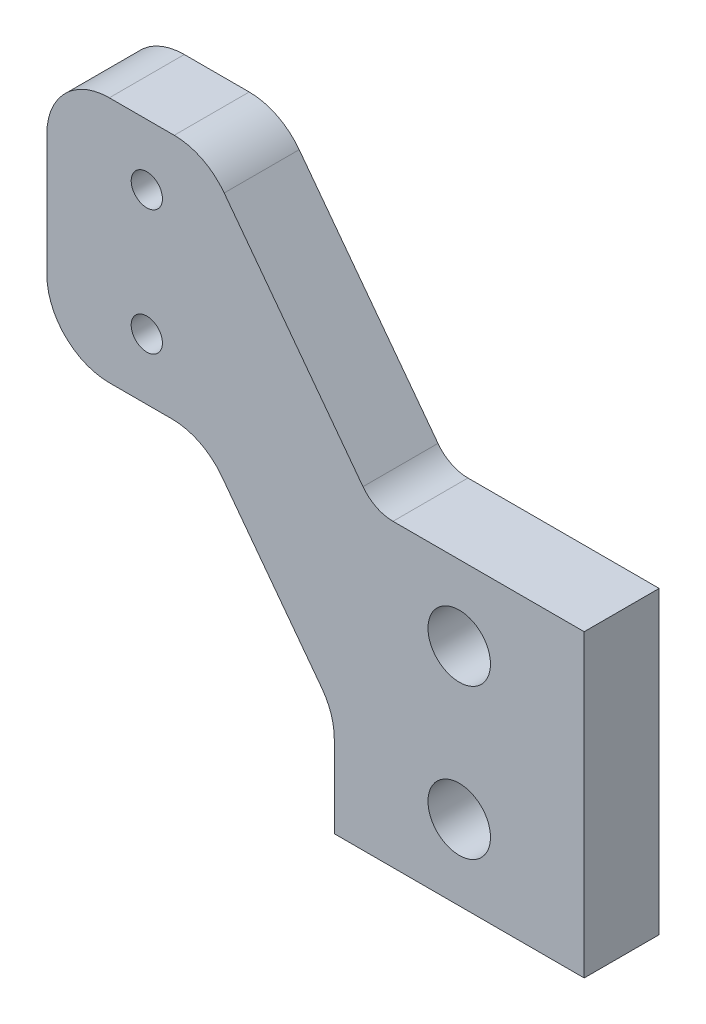
SolidWorks part; units mm, degrees
ref_plane "前视基准面" through (0, 0, 0) normal (0, 0, 1) x (1, 0, 0)
ref_plane "上视基准面" through (0, 0, 0) normal (0, 1, 0) x (1, 0, 0)
ref_plane "右视基准面" through (0, 0, 0) normal (1, 0, 0) x (0, 0, -1)
other "Configuration Table"
sketch "草图1" plane through (0, 0, 0) normal (0, 0, 1) x (1, 0, 0)
  line L0 (1.5, -1.9992) -> (12.6059, -16.8005)
  line L1 (30.3064, -32.6149) -> (30.3064, -42)
  line L2 (30.3064, -42) -> (10.3064, -42)
  line L3 (10.3064, -42) -> (10.3064, -35.3975)
  line L4 (9.3057, -32.3967) -> (1.3166, -21.7492)
  line L5 (-2.6828, -19.75) -> (-7.6936, -19.75)
  line L6 (-12.6936, -14.75) -> (-12.6936, -5)
  line L7 (-7.6936, 0) -> (-2.4993, 0)
  line L9 (15.0055, -18) -> (30.3064, -18)
  line L10 (30.3064, -18) -> (30.3064, -32.6149)
  circle A0 centre (20.3064, -36) radius 2.5
  circle A1 centre (20.3064, -24) radius 2.5
  arc A2 (15.0055, -18) -> (12.6059, -16.8005) centre (15.0055, -15) cw
  circle A3 centre (-4.6936, -4.875) radius 1.25
  circle A4 centre (-4.6936, -14.875) radius 1.25
  arc A5 (10.3064, -35.3975) -> (9.3057, -32.3967) centre (5.3064, -35.3975) ccw
  arc A6 (1.3166, -21.7492) -> (-2.6828, -19.75) centre (-2.6828, -24.75) ccw
  arc A7 (-7.6936, -19.75) -> (-12.6936, -14.75) centre (-7.6936, -14.75) cw
  arc A8 (-12.6936, -5) -> (-7.6936, 0) centre (-7.6936, -5) cw
  arc A9 (1.5, -1.9992) -> (-2.4993, 0) centre (-2.4993, -5) ccw
  point P17 (13.5059, -18)
  point P24 (10.3064, -33.7303)
  point P33 (0, 0)
  dimension "D5" = 5
  dimension "D6" = 5
  dimension "D9" = 3
  dimension "D11" = 2.5
  dimension "D12" = 2.5
  dimension "D17" = 5
  dimension "D18" = 5
  dimension "D1" = 20
  dimension "D2" = 18
  dimension "D3" = 8.2697
  dimension "D4" = 24
  dimension "D7" = 6
  dimension "D8" = 6
  dimension "D10" = 19.75
  dimension "D13" = 10
  dimension "D14" = 4.875
  dimension "D15" = 15
  dimension "D16" = 23
extrude "凸台-拉伸1" add sketch "草图1" along normal blind 6
